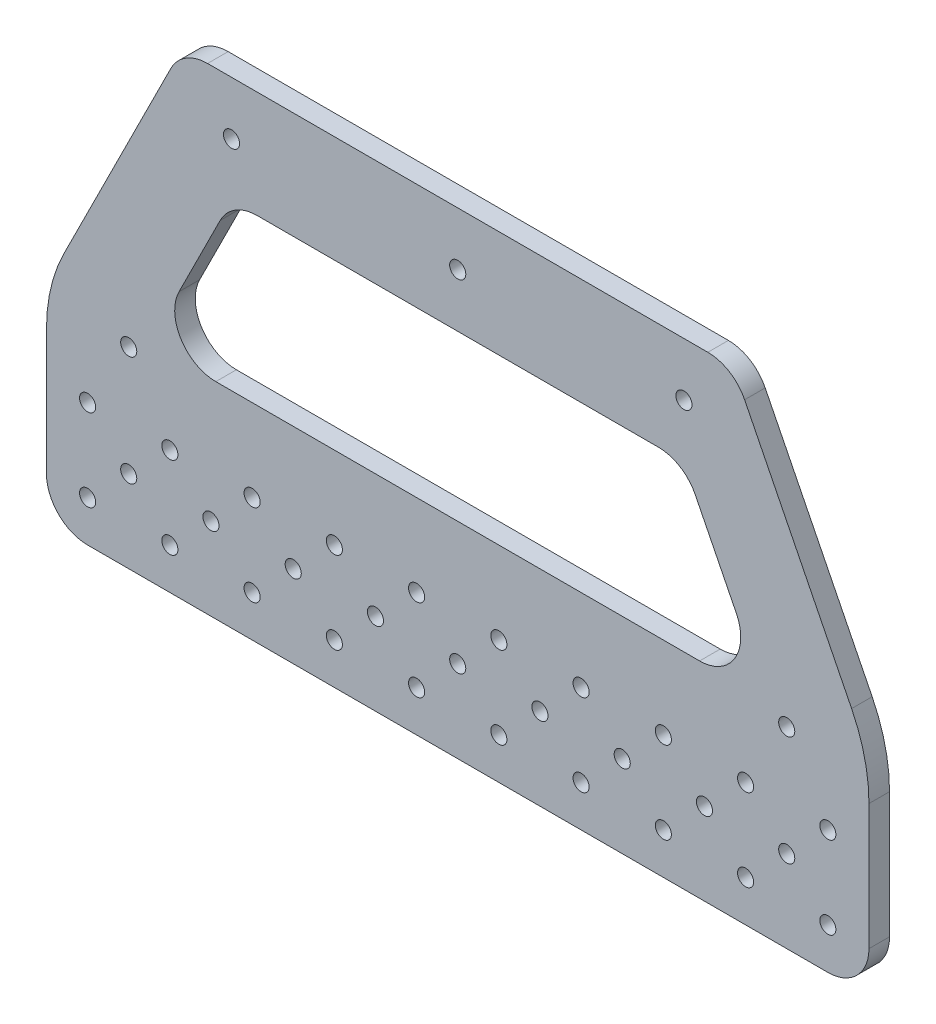
SolidWorks part; units mm, degrees
material "PC High Viscosity"
ref_plane "Front Plane" through (0, 0, 0) normal (0, 0, 1) x (1, 0, 0)
ref_plane "Top Plane" through (0, 0, 0) normal (0, 1, 0) x (1, 0, 0)
ref_plane "Right Plane" through (0, 0, 0) normal (1, 0, 0) x (0, 0, -1)
sketch "Sketch1" plane through (0, 0, 0) normal (0, 0, 1) x (1, 0, 0)
  line L0 (40.9398, 81.8796) -> (53.6398, 107.2796)
  line L1 (12.7, 0) -> (241.3, 0)
  line L2 (0, 12.7) -> (0, 51.5077)
  line L3 (52.299, 63.5) -> (201.701, 63.5)
  line L4 (254, 12.7) -> (254, 51.5077)
  line L5 (57.15, 63.5) -> (196.85, 63.5)
  line L6 (57.15, 63.5) -> (57.15, 114.3) construction
  line L7 (64.999, 114.3) -> (189.001, 114.3)
  line L8 (196.85, 63.5) -> (196.85, 114.3) construction
  line L9 (213.0602, 81.8796) -> (200.3602, 107.2796)
  line L10 (5.3631, 74.2262) -> (38.3998, 140.2996)
  line L11 (49.759, 147.32) -> (204.241, 147.32)
  line L12 (215.6002, 140.2996) -> (248.6369, 74.2262)
  line L13 (0, 63.5) -> (31.75, 63.5) construction
  line L14 (222.25, 63.5) -> (254, 63.5) construction
  arc A0 (204.241, 147.32) -> (215.6002, 140.2996) centre (204.241, 134.62) cw
  arc A1 (38.3998, 140.2996) -> (49.759, 147.32) centre (49.759, 134.62) cw
  arc A2 (189.001, 114.3) -> (200.3602, 107.2796) centre (189.001, 101.6) cw
  arc A3 (213.0602, 81.8796) -> (201.701, 63.5) centre (201.701, 76.2) cw
  arc A4 (40.9398, 81.8796) -> (52.299, 63.5) centre (52.299, 76.2) ccw
  arc A5 (53.6398, 107.2796) -> (64.999, 114.3) centre (64.999, 101.6) cw
  arc A6 (248.6369, 74.2262) -> (254, 51.5077) centre (203.2, 51.5077) cw
  arc A7 (0, 51.5077) -> (5.3631, 74.2262) centre (50.8, 51.5077) cw
  arc A8 (241.3, 0) -> (254, 12.7) centre (241.3, 12.7) ccw
  arc A9 (12.7, 0) -> (0, 12.7) centre (12.7, 12.7) cw
  point P40 (254, 0)
  point P43 (0, 0)
  dimension "D9" = 12.7
  dimension "D10" = 50.8
  dimension "D11" = 12.7
  dimension "D1" = 63.5
  dimension "D2" = 254
  dimension "D3" = 50.8
  dimension "D4" = 139.7
  dimension "D5" = 57.15
  dimension "D6" = 25.4
  dimension "D7" = 25.4
  dimension "D8" = 33.02
extrude "Boss-Extrude1" add sketch "Sketch1" along normal blind 6.35 contours A1 L10 L2 L1 L4 L12 A0 L11 L0 A5 L7 A2 L9 A3 L3 A4
sketch "Sketch2" plane through (0, 0, 6.35) normal (0, 0, 1) x (1, 0, 0)
  line L0 (12.7, 0) -> (241.3, 0) construction
  line L1 (254, 12.7) -> (254, 51.5077) construction
  line L2 (241.3, 12.7) -> (215.9, 12.7) construction
  line L3 (241.3, 12.7) -> (241.3, 38.1) construction
  line L4 (25.4, 25.4) -> (50.8, 25.4) construction
  circle A0 centre (241.3, 12.7) radius 2.4892
  circle A1 centre (215.9, 12.7) radius 2.4892
  circle A2 centre (190.5, 12.7) radius 2.4892
  circle A3 centre (165.1, 12.7) radius 2.4892
  circle A4 centre (139.7, 12.7) radius 2.4892
  circle A5 centre (114.3, 12.7) radius 2.4892
  circle A6 centre (88.9, 12.7) radius 2.4892
  circle A7 centre (63.5, 12.7) radius 2.4892
  circle A8 centre (38.1, 12.7) radius 2.4892
  circle A9 centre (12.7, 12.7) radius 2.4892
  circle A10 centre (215.9, 38.1) radius 2.4892
  circle A11 centre (190.5, 38.1) radius 2.4892
  circle A12 centre (165.1, 38.1) radius 2.4892
  circle A13 centre (139.7, 38.1) radius 2.4892
  circle A14 centre (114.3, 38.1) radius 2.4892
  circle A15 centre (88.9, 38.1) radius 2.4892
  circle A16 centre (63.5, 38.1) radius 2.4892
  circle A17 centre (38.1, 38.1) radius 2.4892
  circle A18 centre (12.7, 38.1) radius 2.4892
  circle A19 centre (241.3, 38.1) radius 2.4892
  circle A20 centre (25.4, 25.4) radius 2.4892
  circle A21 centre (50.8, 25.4) radius 2.4892
  circle A22 centre (76.2, 25.4) radius 2.4892
  circle A23 centre (101.6, 25.4) radius 2.4892
  circle A24 centre (127, 25.4) radius 2.4892
  circle A25 centre (152.4, 25.4) radius 2.4892
  circle A26 centre (177.8, 25.4) radius 2.4892
  circle A27 centre (203.2, 25.4) radius 2.4892
  circle A28 centre (228.6, 25.4) radius 2.4892
  dimension "D1" = 4.9784
  dimension "D2" = 12.7
  dimension "D3" = 12.7
  dimension "D8" = 12.7
  dimension "D9" = 12.7
  dimension "D6" = 25.4
  dimension "D7" = 25.4
  dimension "D11" = 25.4
  dimension "D4" = 10
  dimension "D5" = 2
  dimension "D10" = 9
extrude "Cut-Extrude1" cut sketch "Sketch2" against normal through all
sketch "Sketch3" plane through (0, 0, 6.35) normal (0, 0, 1) x (1, 0, 0)
  line L0 (127, 0) -> (127, 147.32) construction
  line L1 (12.7, 0) -> (241.3, 0) construction
  line L2 (49.759, 147.32) -> (204.241, 147.32) construction
  line L3 (201.701, 76.2) -> (228.6, 59.3327) construction
  circle A0 centre (25.4, 59.3327) radius 2.4892
  circle A1 centre (57.15, 130.81) radius 2.4892
  circle A2 centre (196.85, 130.81) radius 2.4892
  circle A3 centre (228.6, 59.3327) radius 2.4892
  circle A4 centre (127, 130.81) radius 2.4892
  arc A5 (201.701, 63.5) -> (213.0602, 81.8796) centre (201.701, 76.2) ccw construction
  arc A6 (201.701, 63.5) -> (213.0602, 81.8796) centre (201.701, 76.2) ccw
  point P16 (0, 0)
  point P17 (57.15, 132.3442)
  dimension "D3" = 4.9784
  dimension "D4" = 101.6
  dimension "D5" = 101.6
  dimension "D7" = 16.51
  dimension "D1" = 69.85
  dimension "D2" = 69.85
  dimension "D6" = 31.75
extrude "Cut-Extrude2" cut sketch "Sketch3" against normal through all contours A1 | A4 | A2 | A3 | A0
